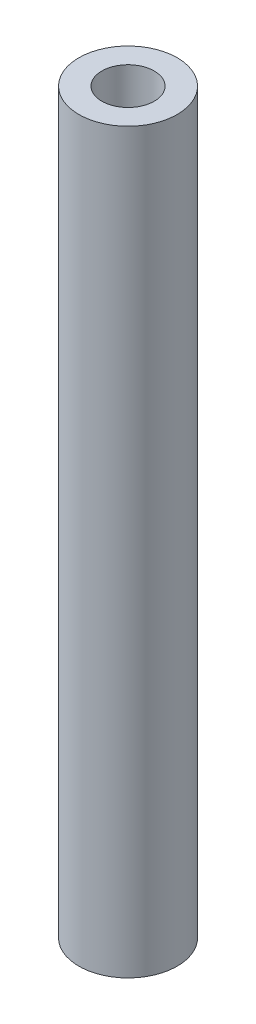
SolidWorks part; units mm, degrees
material "Thornel VCB-20 Carbon Cloth"
ref_plane "Front Plane" through (0, 0, 0) normal (0, 0, 1) x (1, 0, 0)
ref_plane "Top Plane" through (0, 0, 0) normal (0, 1, 0) x (1, 0, 0)
ref_plane "Right Plane" through (0, 0, 0) normal (1, 0, 0) x (0, 0, -1)
sketch "Sketch1" plane through (0, 0, 0) normal (0, 1, 0) x (1, 0, 0)
  circle A0 centre (0, 0) radius 1.6
  circle A1 centre (0, 0) radius 3
  dimension "D1" = 3.2
  dimension "D2" = 6
extrude "Boss-Extrude1" add sketch "Sketch1" along normal blind 45
